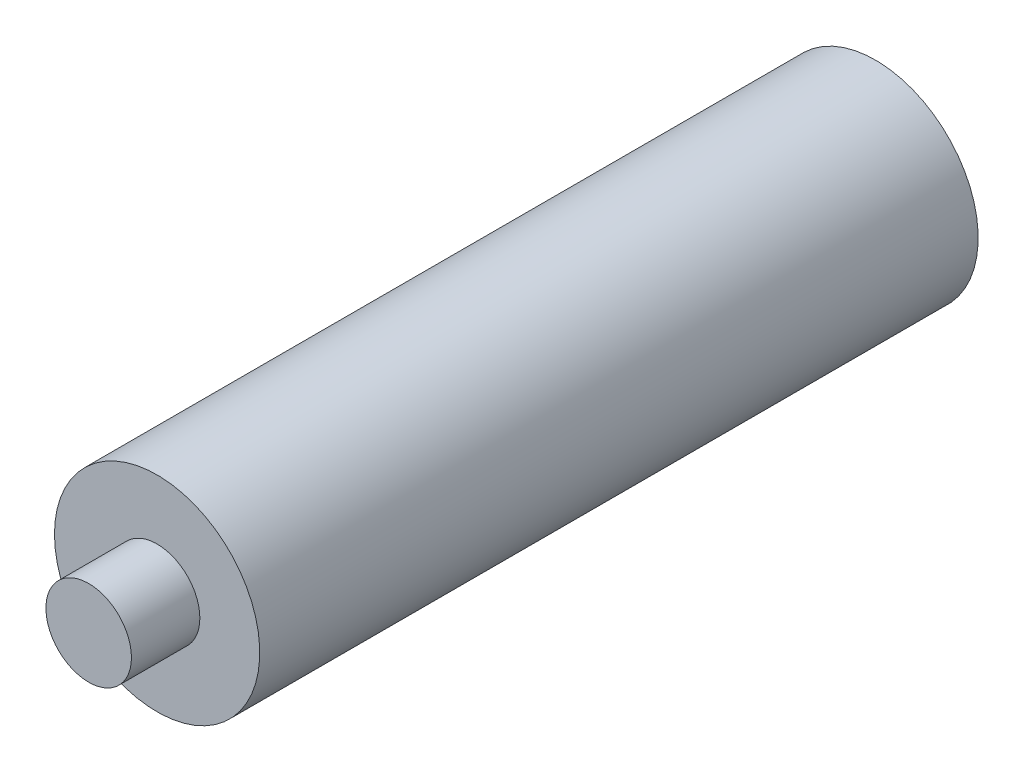
SolidWorks part; units mm, degrees
material "ABS PC"
ref_plane "Front Plane" through (0, 0, 0) normal (0, 0, 1) x (1, 0, 0)
ref_plane "Top Plane" through (0, 0, 0) normal (0, 1, 0) x (1, 0, 0)
ref_plane "Right Plane" through (0, 0, 0) normal (1, 0, 0) x (0, 0, -1)
sketch "Sketch1" plane through (0, 0, 0) normal (0, 0, 1) x (1, 0, 0)
  circle A0 centre (0, 0) radius 3
extrude "Boss-Extrude1" add sketch "Sketch1" along normal blind 21
sketch "Sketch2" plane through (0, 0, 21) normal (0, 0, 1) x (1, 0, 0)
  circle A0 centre (0, 0) radius 1.25
extrude "Boss-Extrude2" add sketch "Sketch2" along normal blind 2
